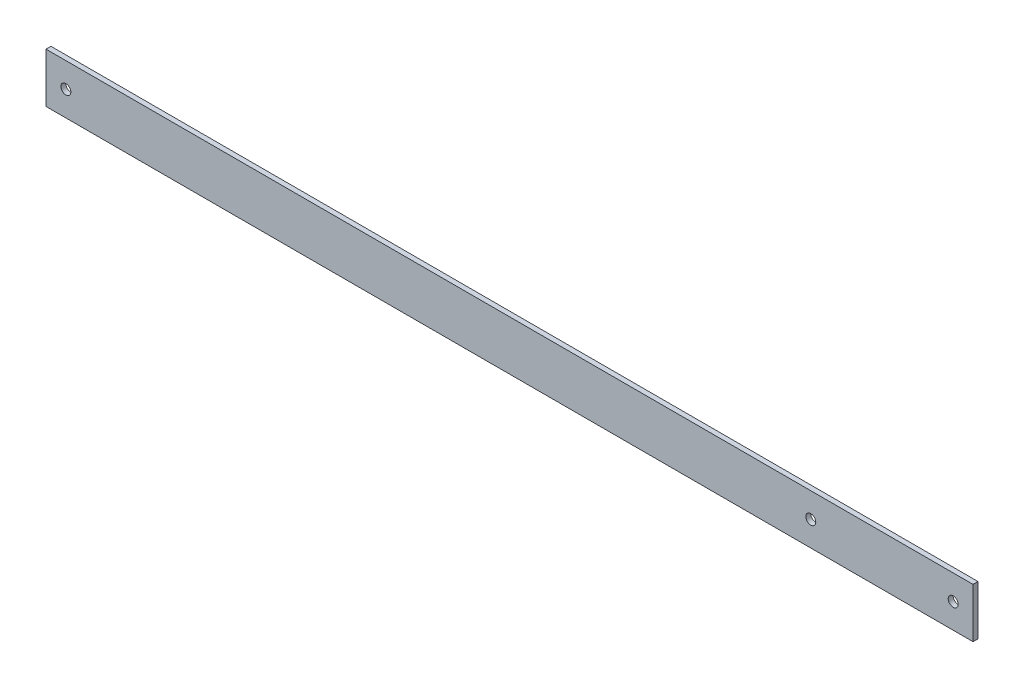
SolidWorks part; units mm, degrees
ref_plane "Plan de face" through (0, 0, 0) normal (0, 0, 1) x (1, 0, 0)
ref_plane "Plan de dessus" through (0, 0, 0) normal (0, 1, 0) x (1, 0, 0)
ref_plane "Plan de droite" through (0, 0, 0) normal (1, 0, 0) x (0, 0, -1)
sketch "Esquisse1" plane through (0, 0, 0) normal (0, 0, 1) x (1, 0, 0)
  line L1 (-286.9096, 1668.032) -> (-6.9096, 1668.032)
  line L2 (-286.9096, 1668.032) -> (-286.9096, 1683.032)
  line L3 (-286.9096, 1683.032) -> (-6.9096, 1683.032)
  line L4 (-6.9096, 1668.032) -> (-6.9096, 1683.032)
  dimension "D1" = 280
  dimension "D2" = 15
extrude "Extrusion1" add sketch "Esquisse1" along normal blind 1.5
sketch "Esquisse2" plane through (0, 0, 0) normal (0, 0, -1) x (-1, 0, 0)
  line L0 (286.9096, 1683.032) -> (286.9096, 1668.032) construction
  line L1 (6.9096, 1668.032) -> (6.9096, 1683.032) construction
  line L2 (6.9096, 1683.032) -> (286.9096, 1683.032) construction
  line L3 (286.9096, 1668.032) -> (6.9096, 1668.032) construction
  circle A0 centre (280.9096, 1675.532) radius 1.5
  circle A1 centre (12.9096, 1675.532) radius 1.5
  circle A2 centre (55.9096, 1675.532) radius 1.5
  point P6 (6.9096, 1675.532)
  dimension "D1" = 6
  dimension "D2" = 6
  dimension "D5" = 49
  dimension "D3" = 7.5
  dimension "D4" = 7.5
extrude "Extrusion2" cut sketch "Esquisse2" against normal blind 1.5
